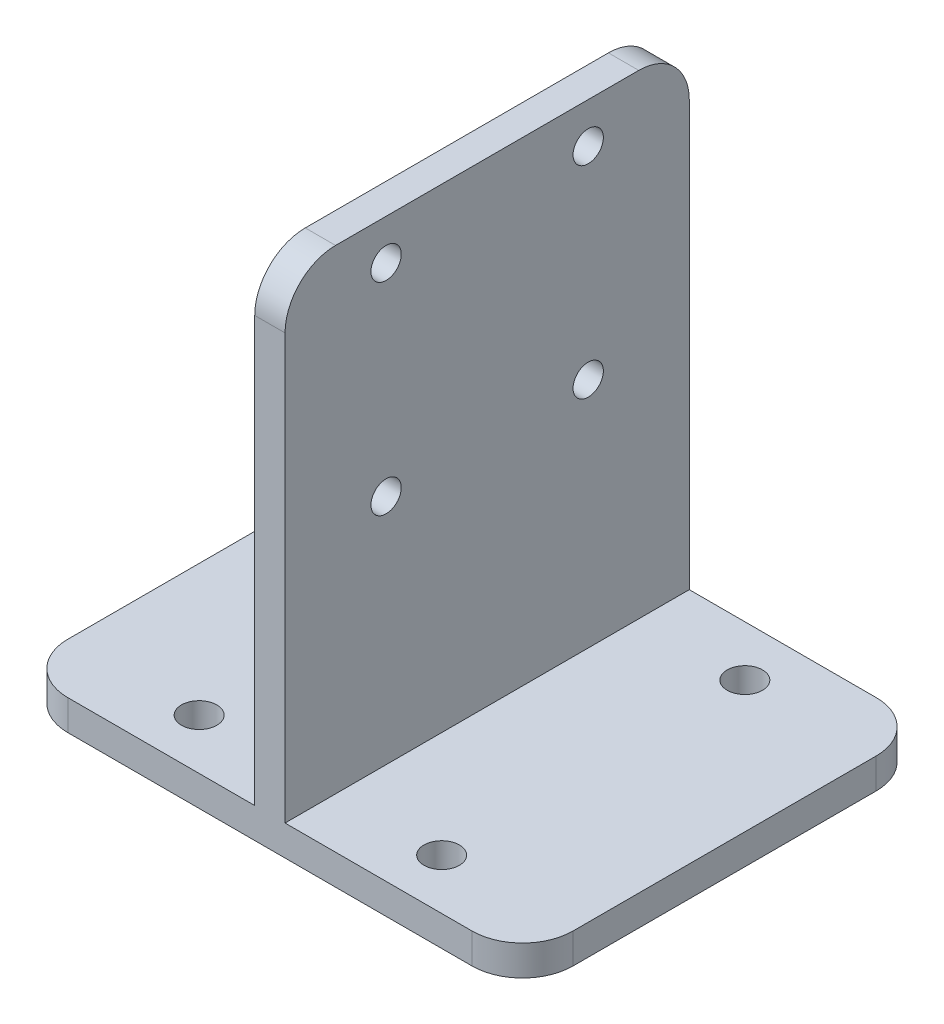
SolidWorks part; units mm, degrees
ref_plane "前视基准面" through (0, 0, 0) normal (0, 0, 1) x (1, 0, 0)
ref_plane "上视基准面" through (0, 0, 0) normal (0, 1, 0) x (1, 0, 0)
ref_plane "右视基准面" through (0, 0, 0) normal (1, 0, 0) x (0, 0, -1)
other "Configuration Table"
sketch "草图1" plane through (0, 0, 0) normal (0, 1, 0) x (1, 0, 0)
  line L1 (-12, -15) -> (12, -15) construction
  line L2 (-12, -15) -> (-12, 15) construction
  line L3 (-12, 15) -> (12, 15) construction
  line L4 (12, -15) -> (12, 15) construction
  line L5 (-12, -15) -> (12, 15) construction
  line L6 (-12, 15) -> (12, -15) construction
  line L7 (-25, -20) -> (25, -20)
  line L8 (-25, -20) -> (-25, 20)
  line L9 (-25, 20) -> (25, 20)
  line L10 (25, -20) -> (25, 20)
  line L11 (-25, -20) -> (25, 20) construction
  line L12 (-25, 20) -> (25, -20) construction
  circle A0 centre (-12, 15) radius 1.75
  circle A1 centre (12, 15) radius 1.75
  circle A2 centre (12, -15) radius 1.75
  circle A3 centre (-12, -15) radius 1.75
  point P0 (0, 0)
  point P6 (0, 0)
  dimension "D5" = 3.5
  dimension "D6" = 3.5
  dimension "D7" = 3.5
  dimension "D8" = 3.5
  dimension "D1" = 24
  dimension "D2" = 30
  dimension "D3" = 50
  dimension "D4" = 40
extrude "凸台-拉伸1" add sketch "草图1" along normal blind 3
fillet "圆角1" radius 5 4 edges at (-25, 1.5, -20) (25, 1.5, -20) (25, 1.5, 20) (-25, 1.5, 20)
sketch "草图2" plane through (0, 3, 0) normal (0, 1, 0) x (1, 0, 0)
  line L0 (20, 20) -> (-20, 20) construction
  line L1 (-1.5, -20) -> (1.5, -20)
  line L2 (-1.5, -20) -> (-1.5, 20)
  line L3 (-1.5, 20) -> (1.5, 20)
  line L4 (1.5, -20) -> (1.5, 20)
  line L5 (-1.5, -20) -> (1.5, 20) construction
  line L6 (-1.5, 20) -> (1.5, -20) construction
  point P0 (0, 0)
  dimension "D1" = 3
extrude "凸台-拉伸2" add sketch "草图2" along normal blind 47
sketch "草图3" plane through (-1.5, 0, 0) normal (-1, 0, 0) x (0, 0, 1)
  line L0 (-20, 3) -> (20, 3) construction
  line L1 (-20, 3) -> (20, 3) construction
  line L2 (-20, 50) -> (20, 50) construction
  line L3 (0, 0) -> (0, 14.4294) construction
  line L4 (-10, 26) -> (10, 26) construction
  line L5 (-10, 26) -> (-10, 46) construction
  line L6 (-10, 46) -> (10, 46) construction
  line L7 (10, 26) -> (10, 46) construction
  line L8 (-10, 26) -> (10, 46) construction
  line L9 (-10, 46) -> (10, 26) construction
  circle A1 centre (-10, 46) radius 1.5
  circle A2 centre (10, 46) radius 1.5
  circle A3 centre (10, 26) radius 1.5
  circle A4 centre (-10, 26) radius 1.5
  point P15 (0, 36)
  dimension "D1" = 4
  dimension "D4" = 3
  dimension "D5" = 3
  dimension "D6" = 3
  dimension "D7" = 3
  dimension "D2" = 20
  dimension "D3" = 20
  dimension "D8" = 33
extrude "切除-拉伸1" cut sketch "草图3" against normal up to next
fillet "圆角2" radius 5 2 edges at (0, 50, 20) (0, 50, -20)
